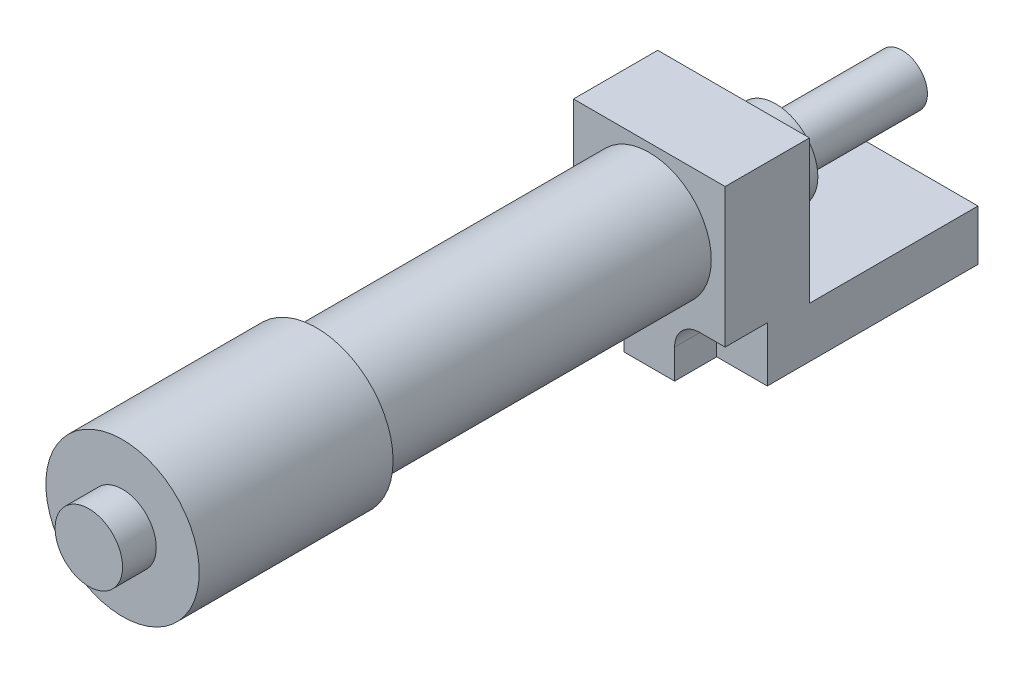
SolidWorks part; units mm, degrees
ref_plane "Front Plane" through (0, 0, 0) normal (0, 0, 1) x (1, 0, 0)
ref_plane "Top Plane" through (0, 0, 0) normal (0, 1, 0) x (1, 0, 0)
ref_plane "Right Plane" through (0, 0, 0) normal (1, 0, 0) x (0, 0, -1)
sketch "Sketch1" plane through (0, 0, 0) normal (1, 0, 0) x (0, 0, -1)
  line L0 (0, 0) -> (30, 0)
  line L1 (30, 0) -> (30, 6)
  line L2 (30, 6) -> (10, 6)
  line L3 (10, 6) -> (10, 23)
  line L4 (10, 23) -> (0, 23)
  line L5 (0, 23) -> (0, 0)
  dimension "D1" = 30
  dimension "D2" = 23
  dimension "D3" = 6
  dimension "D4" = 10
extrude "Boss-Extrude1" add sketch "Sketch1" along normal blind 18
sketch "Sketch2" plane through (0, 0, 0) normal (0, 0, 1) x (1, 0, 0)
  line L1 (0, 23) -> (0, 0) construction
  line L2 (18, 0) -> (12, 0) construction
  line L3 (18, 0) -> (18, 6.5) construction
  line L4 (18, 6.5) -> (0, 6.5) construction
  line L5 (0, 0) -> (0, 6.5) construction
  line L6 (9, 6.5) -> (9, 0) construction
  line L8 (12, 0) -> (12, 3.5)
  line L9 (15, 6.5) -> (18, 6.5)
  line L10 (18, 6.5) -> (18, 0)
  line L11 (18, 0) -> (12, 0)
  line L12 (6, 0) -> (6, 3.5)
  line L13 (3, 6.5) -> (0, 6.5)
  line L14 (0, 6.5) -> (0, 0)
  line L15 (0, 0) -> (6, 0)
  line L16 (6, 0) -> (0, 0) construction
  arc A0 (15, 6.5) -> (12, 3.5) centre (15, 3.5) ccw
  arc A1 (3, 6.5) -> (6, 3.5) centre (3, 3.5) cw
  dimension "D3" = 6
  dimension "D1" = 6
  dimension "D2" = 6.5
extrude "Cut-Extrude1" cut sketch "Sketch2" against normal blind 5 contours L12 A1 L13 L14 L15 | L11 L10 L9 A0 L8
sketch "Sketch4" plane through (0, 0, -10) normal (0, 0, -1) x (-1, 0, 0)
  line L0 (-9, 23) -> (-9, 6) construction
  line L1 (0, 14.5) -> (-18, 14.5) construction
  line L4 (0, 6) -> (0, 23)
  line L5 (0, 23) -> (-18, 23)
  line L6 (-18, 23) -> (-18, 6)
  line L7 (-18, 6) -> (0, 6)
  line L8 (0, 6) -> (0, 23) construction
  line L9 (0, 23) -> (-18, 23) construction
  line L10 (-18, 23) -> (-18, 6) construction
  line L11 (-18, 6) -> (0, 6) construction
  circle A0 centre (-9, 14.5) radius 5
  dimension "D2" = 10
  dimension "D1" = 0
extrude "Boss-Extrude2" add sketch "Sketch4" along normal blind 5
sketch "Sketch5" plane through (0, 0, -15) normal (0, 0, -1) x (-1, 0, 0)
  circle A0 centre (-9, 14.5) radius 3
  dimension "D1" = 6
extrude "Boss-Extrude3" add sketch "Sketch5" along normal blind 15
sketch "Sketch6" plane through (0, 0, 0) normal (0, 0, 1) x (1, 0, 0)
  line L0 (9, 23) -> (9, 0) construction
  line L1 (18, 23) -> (0, 23) construction
  line L2 (12, 0) -> (6, 0) construction
  circle A0 centre (9, 14.65) radius 7.35
  point P8 (0, 0)
  point P9 (0, 0)
  dimension "D1" = 14.7
  dimension "D2" = 8.35
extrude "Boss-Extrude4" add sketch "Sketch6" along normal blind 39.5
sketch "Sketch7" plane through (0, 0, 39.5) normal (0, 0, 1) x (1, 0, 0)
  circle A0 centre (9, 14.65) radius 9.1
  dimension "D1" = 18.2
extrude "Boss-Extrude5" add sketch "Sketch7" along normal blind 23
sketch "Sketch8" plane through (0, 0, 62.5) normal (0, 0, 1) x (1, 0, 0)
  circle A0 centre (9, 14.65) radius 4
  point P3 (0, 0)
  dimension "D1" = 8
extrude "Boss-Extrude6" add sketch "Sketch8" along normal blind 4
